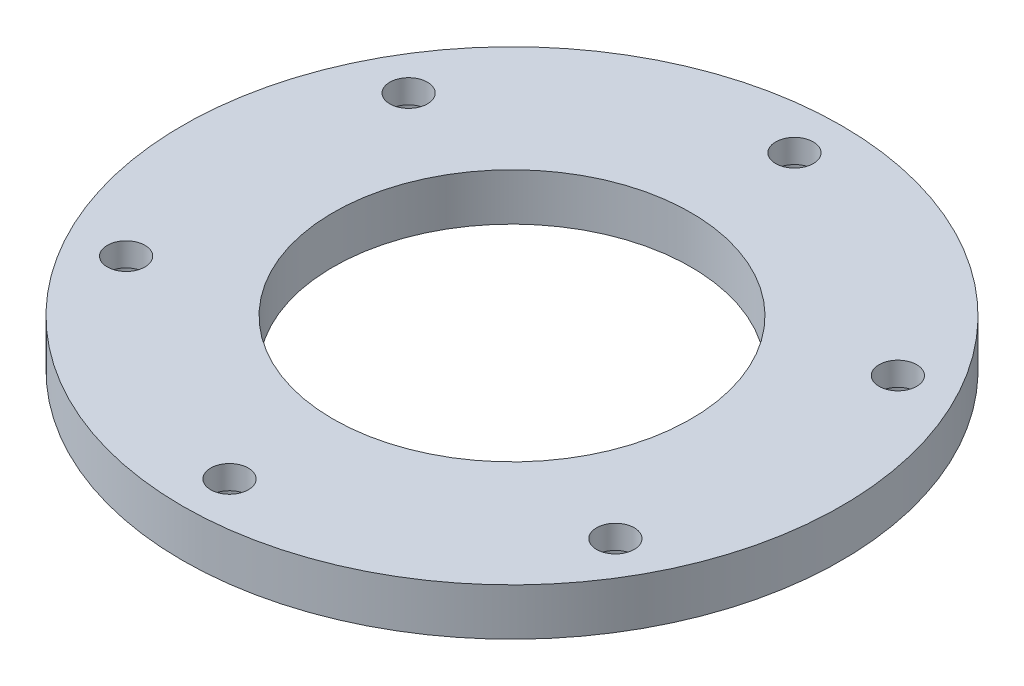
SolidWorks part; units mm, degrees
ref_plane "前视基准面" through (0, 0, 0) normal (0, 0, 1) x (1, 0, 0)
ref_plane "上视基准面" through (0, 0, 0) normal (0, 1, 0) x (1, 0, 0)
ref_plane "右视基准面" through (0, 0, 0) normal (1, 0, 0) x (0, 0, -1)
sketch "草图1" plane through (0, 0, 0) normal (0, 1, 0) x (1, 0, 0)
  circle A0 centre (0, 0) radius 35
  circle A1 centre (0, 0) radius 19
  circle A2 centre (0, 0) radius 30
  circle A3 centre (0, 30) radius 2
  circle A4 centre (25.9808, 15) radius 2
  circle A5 centre (25.9808, -15) radius 2
  circle A6 centre (0, -30) radius 2
  circle A7 centre (-25.9808, -15) radius 2
  circle A8 centre (-25.9808, 15) radius 2
  point P19 (0, 0)
  dimension "D1" = 70
  dimension "D2" = 38
  dimension "D3" = 60
  dimension "D4" = 4
  dimension "D5" = 6
extrude "凸台-拉伸1" add sketch "草图1" along normal blind 5 contours A0 A8 A2 A3 A4 A5 A6 A7 | A8 A2 A7 A6 A5 A4 A3 A1
sketch "草图2" plane through (0, 0, 0) normal (0, -1, 0) x (1, 0, 0)
  circle A0 centre (0, 0) radius 30
  circle A1 centre (0, 30) radius 3.75
  circle A2 centre (25.9808, 15) radius 3.75
  circle A3 centre (25.9808, -15) radius 3.75
  circle A4 centre (0, -30) radius 3.75
  circle A5 centre (-25.9808, -15) radius 3.75
  circle A6 centre (-25.9808, 15) radius 3.75
  point P18 (0, 0)
  dimension "D1" = 7.5
  dimension "D2" = 6
extrude "切除-拉伸1" cut sketch "草图2" against normal blind 2.5 contours A6 | A5 | A4 | A3 | A2 | A1
